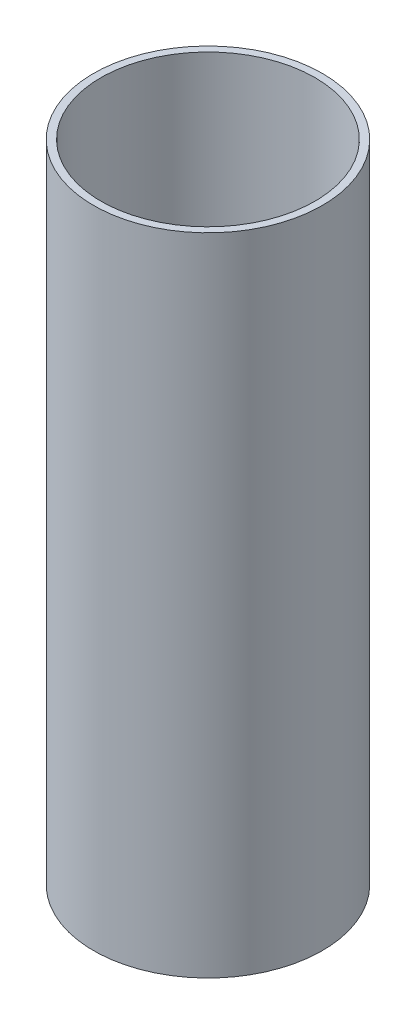
SolidWorks part; units mm, degrees
ref_plane "Front Plane" through (0, 0, 0) normal (0, 0, 1) x (1, 0, 0)
ref_plane "Top Plane" through (0, 0, 0) normal (0, 1, 0) x (1, 0, 0)
ref_plane "Right Plane" through (0, 0, 0) normal (1, 0, 0) x (0, 0, -1)
sketch "Sketch1" plane through (0, 0, 0) normal (0, 0, 1) x (1, 0, 0)
  line L1 (46.355, 0) -> (49.53, 0)
  line L2 (46.355, 0) -> (46.355, 279.4)
  line L3 (46.355, 279.4) -> (49.53, 279.4)
  line L4 (49.53, 0) -> (49.53, 279.4)
  point P4 (48.8862, 7.9601)
  point P6 (56.8083, 11.7271)
  point P7 (0, 0)
  dimension "D1" = 49.53
  dimension "D2" = 3.175
  dimension "D3" = 279.4
  dimension "D4" = 0
ref_axis "Axis1" through (0, -13.97, 0) along (0, 1, 0)
revolve "Revolve1" add sketch "Sketch1" angle 360 about axis through (0, -13.97, 0) along (0, 1, 0)
